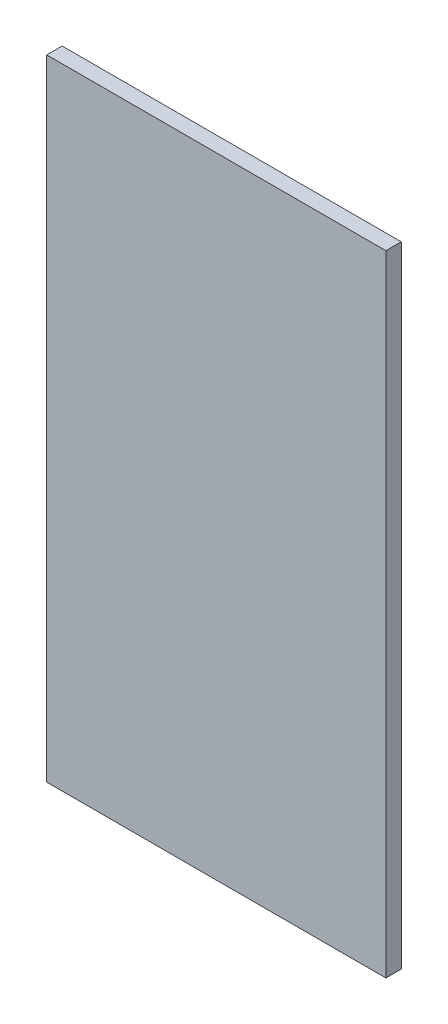
SolidWorks part; units mm, degrees
ref_plane "Front Plane" through (0, 0, 0) normal (0, 0, 1) x (1, 0, 0)
ref_plane "Top Plane" through (0, 0, 0) normal (0, 1, 0) x (1, 0, 0)
ref_plane "Right Plane" through (0, 0, 0) normal (1, 0, 0) x (0, 0, -1)
sketch "Sketch1" plane through (0, 0, 0) normal (0, 0, 1) x (1, 0, 0)
  line L1 (-50, 2.5) -> (-15, 2.5)
  line L2 (-50, 2.5) -> (-50, 67.5)
  line L3 (-50, 67.5) -> (-15, 67.5)
  line L4 (-15, 2.5) -> (-15, 67.5)
  line L5 (-50.5, 69) -> (-14.5, 69) construction
  line L6 (-50.5, 1) -> (-50.5, 69) construction
  point P4 (0, 0)
  point P7 (-32.5, 69)
  point P8 (-32.5, 67.5)
  point P11 (-50.5, 35)
  point P12 (-50, 35)
  dimension "D1" = 35
  dimension "D2" = 65
extrude "Boss-Extrude1" add sketch "Sketch1" along normal blind 1.5875
